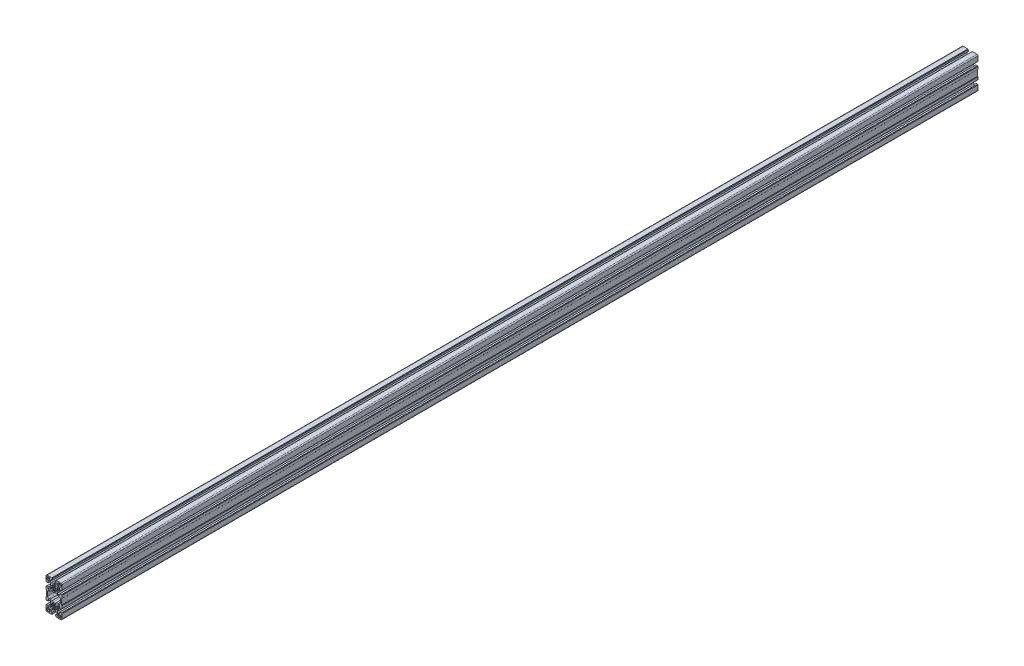
SolidWorks part; units mm, degrees
material "3.1355 (EN-AW 2024)"
ref_plane "Спереди" through (0, 0, 0) normal (0, 0, 1) x (1, 0, 0)
ref_plane "Сверху" through (0, 0, 0) normal (0, 1, 0) x (1, 0, 0)
ref_plane "Справа" through (0, 0, 0) normal (1, 0, 0) x (0, 0, -1)
sketch "Model" plane through (0, 0, 0) normal (0, 0, 1) x (1, 0, 0)
  line L360 (15.75, -42.1999) -> (15.4036, -41.9999)
  line L361 (15.4036, -41.9999) -> (13, -41.9999)
  line L362 (12, -41) -> (12, -35.5)
  line L363 (13, -34.5) -> (18.5, -34.5)
  line L364 (19.5, -35.5) -> (19.5, -41)
  line L365 (18.5, -41.9999) -> (16.0964, -41.9999)
  line L366 (16.0964, -41.9999) -> (15.75, -42.1999)
  line L367 (-19.4998, 35.4999) -> (-19.4998, 40.9999)
  line L368 (-18.4998, 41.9998) -> (-12.9998, 41.9998)
  line L369 (-11.9998, 40.9999) -> (-11.9998, 35.4999)
  line L370 (-12.9998, 34.4999) -> (-18.4998, 34.4999)
  line L371 (0.8683, -17.576) -> (1.3893, -14.6216)
  line L372 (4.5887, -15.9468) -> (2.8679, -18.4043)
  line L373 (4.0958, -19.6321) -> (6.5533, -17.9114)
  line L374 (7.8785, -21.1108) -> (4.9241, -21.6318)
  line L375 (4.9241, -23.3682) -> (7.8785, -23.8892)
  line L376 (6.5533, -27.0886) -> (4.0958, -25.3679)
  line L377 (2.868, -26.5958) -> (4.5887, -29.0532)
  line L378 (1.3893, -30.3784) -> (0.8683, -27.424)
  line L379 (-0.8682, -27.424) -> (-1.3891, -30.3785)
  line L380 (-4.5885, -29.0532) -> (-2.8678, -26.5958)
  line L381 (-4.0957, -25.3679) -> (-6.5531, -27.0886)
  line L382 (-7.8784, -23.8892) -> (-4.924, -23.3682)
  line L383 (-4.924, -21.6318) -> (-7.8784, -21.1108)
  line L384 (-6.5531, -17.9114) -> (-4.0957, -19.6321)
  line L385 (-2.8678, -18.4043) -> (-4.5885, -15.9468)
  line L386 (-1.3891, -14.6216) -> (-0.8682, -17.576)
  line L387 (14, -9.4501) -> (11.0574, -9.4501)
  line L388 (11.0574, -9.4501) -> (7.5074, -13.0001)
  line L389 (7.5074, -13.0001) -> (3.1226, -13.0001)
  line L390 (-3.1223, -13) -> (-7.5073, -13)
  line L391 (-7.5073, -13) -> (-11.0573, -9.4501)
  line L392 (-11.0573, -9.4501) -> (-13.9999, -9.4501)
  line L393 (-17.9999, -5.4501) -> (-17.9999, -5.45)
  line L394 (-17.9999, -5.45) -> (-17.9999, 5.45)
  line L395 (-13.9999, 9.45) -> (-11.0573, 9.45)
  line L396 (-11.0573, 9.45) -> (-7.5073, 12.9999)
  line L397 (-7.5073, 12.9999) -> (-3.1223, 12.9999)
  line L398 (3.1226, 13) -> (7.5074, 13)
  line L399 (7.5074, 13) -> (11.0574, 9.45)
  line L400 (11.0574, 9.45) -> (14, 9.45)
  line L401 (18, 5.4499) -> (18, -5.4501)
  line L402 (1.3893, 14.6215) -> (0.8683, 17.5759)
  line L403 (-0.8682, 17.5759) -> (-1.3891, 14.6215)
  line L404 (-4.5885, 15.9467) -> (-2.8678, 18.4042)
  line L405 (-4.0957, 19.632) -> (-6.5531, 17.9113)
  line L406 (-7.8784, 21.1107) -> (-4.924, 21.6317)
  line L407 (-4.924, 23.3681) -> (-7.8784, 23.8891)
  line L408 (-6.5531, 27.0885) -> (-4.0957, 25.3678)
  line L409 (-2.8678, 26.5957) -> (-4.5885, 29.0531)
  line L410 (-1.3891, 30.3784) -> (-0.8682, 27.4239)
  line L411 (0.8683, 27.4239) -> (1.3893, 30.3783)
  line L412 (4.5887, 29.0531) -> (2.868, 26.5957)
  line L413 (4.0958, 25.3678) -> (6.5533, 27.0885)
  line L414 (7.8785, 23.8891) -> (4.9241, 23.3681)
  line L415 (4.9241, 21.6317) -> (7.8785, 21.1107)
  line L416 (6.5533, 17.9113) -> (4.0958, 19.632)
  line L417 (2.8679, 18.4042) -> (4.5887, 15.9467)
  line L418 (18.5, 34.4999) -> (13, 34.4999)
  line L419 (12, 35.4999) -> (12, 40.9999)
  line L420 (13, 41.9998) -> (18.5, 41.9998)
  line L421 (19.5, 40.9999) -> (19.5, 35.4999)
  line L422 (-18.4998, -34.5) -> (-12.9998, -34.5)
  line L423 (-11.9998, -35.5) -> (-11.9998, -41)
  line L424 (-12.9998, -41.9999) -> (-18.4998, -41.9999)
  line L425 (-19.4998, -41) -> (-19.4998, -35.5)
  line L426 (-9.9671, -21.6906) -> (-9.4999, -22.4998)
  line L427 (-9.4999, -22.4998) -> (-9.9671, -23.3091)
  line L428 (-9.4999, -25.6225) -> (-9.4999, -29.7069)
  line L429 (-9.4999, -29.7069) -> (-12.3428, -32.5498)
  line L430 (-12.3428, -32.5498) -> (-16.4999, -32.5498)
  line L431 (-16.4999, -32.5498) -> (-16.4999, -27.6503)
  line L432 (-16.4999, -27.6503) -> (-20.9999, -27.6503)
  line L433 (-20.9999, -27.6503) -> (-20.9999, -28.2998)
  line L434 (-20.9999, -28.2998) -> (-22, -28.2998)
  line L435 (-22.5, -28.7998) -> (-22.5, -42.0001)
  line L436 (-19.5, -45.0001) -> (-6.3001, -45.0001)
  line L437 (-5.8001, -44.5001) -> (-5.8001, -43.4999)
  line L438 (-5.8001, -43.4999) -> (-5.15, -43.4999)
  line L439 (-5.15, -43.4999) -> (-5.15, -39)
  line L440 (-5.15, -39) -> (-10.05, -39)
  line L441 (-10.05, -39) -> (-10.05, -34.8429)
  line L442 (-10.05, -34.8429) -> (-7.207, -31.9999)
  line L443 (-7.207, -31.9999) -> (-3.1227, -31.9999)
  line L444 (-0.8092, -32.4672) -> (0, -32)
  line L445 (0, -32) -> (0.8092, -32.4672)
  line L446 (3.1227, -31.9999) -> (7.207, -31.9999)
  line L447 (7.207, -31.9999) -> (10.05, -34.8429)
  line L448 (10.05, -34.8429) -> (10.05, -39)
  line L449 (10.05, -39) -> (5.1501, -39)
  line L450 (5.1501, -39) -> (5.1501, -43.4999)
  line L451 (5.1501, -43.4999) -> (5.8002, -43.4999)
  line L452 (5.8002, -43.4999) -> (5.8002, -44.5001)
  line L453 (6.3002, -45.0001) -> (19.5001, -45.0001)
  line L454 (22.5, -42.0001) -> (22.5, -28.8001)
  line L455 (22, -28.3001) -> (21.0001, -28.3001)
  line L456 (21.0001, -28.3001) -> (21.0001, -27.6501)
  line L457 (21.0001, -27.6501) -> (16.5, -27.6501)
  line L458 (16.5, -27.6501) -> (16.5, -32.5501)
  line L459 (16.5, -32.5501) -> (12.3429, -32.5501)
  line L460 (12.3429, -32.5501) -> (9.5, -29.7071)
  line L461 (9.5, -29.7071) -> (9.5, -25.6228)
  line L462 (9.9672, -23.3093) -> (9.5, -22.5001)
  line L463 (9.5, -22.5001) -> (9.9672, -21.6909)
  line L464 (9.5, -19.3774) -> (9.5, -15.2931)
  line L465 (9.5, -15.2931) -> (12.3429, -12.4501)
  line L466 (12.3429, -12.4501) -> (16.5, -12.4501)
  line L467 (16.5, -12.4501) -> (16.5, -17.3501)
  line L468 (16.5, -17.3501) -> (21, -17.3501)
  line L469 (21, -17.3501) -> (21, -16.7)
  line L470 (21, -16.7) -> (22, -16.7)
  line L471 (22.5, -16.2) -> (22.5, -9.25)
  line L472 (22, -8.75) -> (21, -8.75)
  line L473 (21, -8.75) -> (21, 8.7499)
  line L474 (21, 8.7499) -> (22, 8.7499)
  line L475 (22.5, 9.2499) -> (22.5, 16.1999)
  line L476 (22, 16.6999) -> (21, 16.6999)
  line L477 (21, 16.6999) -> (21, 17.35)
  line L478 (21, 17.35) -> (16.5, 17.35)
  line L479 (16.5, 17.35) -> (16.5, 12.45)
  line L480 (16.5, 12.45) -> (12.3429, 12.45)
  line L481 (12.3429, 12.45) -> (9.5, 15.293)
  line L482 (9.5, 15.293) -> (9.5, 19.3773)
  line L483 (9.9672, 21.6908) -> (9.5, 22.5)
  line L484 (9.5, 22.5) -> (9.9672, 23.3092)
  line L485 (9.5, 25.6227) -> (9.5, 29.707)
  line L486 (9.5, 29.707) -> (12.3429, 32.55)
  line L487 (12.3429, 32.55) -> (16.5, 32.55)
  line L488 (16.5, 32.55) -> (16.5, 27.65)
  line L489 (16.5, 27.65) -> (21, 27.65)
  line L490 (21, 27.65) -> (21, 28.3)
  line L491 (21, 28.3) -> (22, 28.3)
  line L492 (22.5, 28.8) -> (22.5, 42)
  line L493 (19.5001, 44.9999) -> (6.3002, 44.9999)
  line L494 (5.8002, 44.5) -> (5.8002, 43.4998)
  line L495 (5.8002, 43.4998) -> (5.1501, 43.4998)
  line L496 (5.1501, 43.4998) -> (5.1501, 38.9998)
  line L497 (5.1501, 38.9998) -> (10.05, 38.9998)
  line L498 (10.05, 38.9998) -> (10.05, 34.8428)
  line L499 (10.05, 34.8428) -> (7.207, 31.9998)
  line L500 (7.207, 31.9998) -> (3.1227, 31.9998)
  line L501 (0.8092, 32.4671) -> (0, 31.9999)
  line L502 (0, 31.9999) -> (-0.8092, 32.4671)
  line L503 (-3.1227, 31.9998) -> (-7.207, 31.9998)
  line L504 (-7.207, 31.9998) -> (-10.05, 34.8428)
  line L505 (-10.05, 34.8428) -> (-10.05, 38.9998)
  line L506 (-10.05, 38.9998) -> (-5.15, 38.9998)
  line L507 (-5.15, 38.9998) -> (-5.15, 43.4998)
  line L508 (-5.15, 43.4998) -> (-5.8001, 43.4998)
  line L509 (-5.8001, 43.4998) -> (-5.8001, 44.5)
  line L510 (-6.3001, 44.9999) -> (-19.5, 44.9999)
  line L511 (-22.5, 42) -> (-22.5, 28.7997)
  line L512 (-22, 28.2997) -> (-20.9999, 28.2997)
  line L513 (-20.9999, 28.2997) -> (-20.9999, 27.6502)
  line L514 (-20.9999, 27.6502) -> (-16.4999, 27.6502)
  line L515 (-16.4999, 27.6502) -> (-16.4999, 32.5497)
  line L516 (-16.4999, 32.5497) -> (-12.3428, 32.5497)
  line L517 (-12.3428, 32.5497) -> (-9.4999, 29.7068)
  line L518 (-9.4999, 29.7068) -> (-9.4999, 25.6224)
  line L519 (-9.9671, 23.309) -> (-9.4999, 22.4997)
  line L520 (-9.4999, 22.4997) -> (-9.9671, 21.6905)
  line L521 (-9.4999, 19.3771) -> (-9.4999, 15.2927)
  line L522 (-9.4999, 15.2927) -> (-12.3428, 12.4498)
  line L523 (-12.3428, 12.4498) -> (-16.4999, 12.4498)
  line L524 (-16.4999, 12.4498) -> (-16.4999, 17.3498)
  line L525 (-16.4999, 17.3498) -> (-20.9999, 17.3498)
  line L526 (-20.9999, 17.3498) -> (-20.9999, 16.6998)
  line L527 (-20.9999, 16.6998) -> (-22, 16.6998)
  line L528 (-22.5, 16.1998) -> (-22.5, 9.2499)
  line L529 (-22, 8.7499) -> (-21, 8.7499)
  line L530 (-21, 8.7499) -> (-21, -8.75)
  line L531 (-21, -8.75) -> (-22, -8.75)
  line L532 (-22.5, -9.25) -> (-22.5, -16.1999)
  line L533 (-22, -16.6999) -> (-20.9999, -16.6999)
  line L534 (-20.9999, -16.6999) -> (-20.9999, -17.3499)
  line L535 (-20.9999, -17.3499) -> (-16.4999, -17.3499)
  line L536 (-16.4999, -17.3499) -> (-16.4999, -12.4499)
  line L537 (-16.4999, -12.4499) -> (-12.3428, -12.4499)
  line L538 (-12.3428, -12.4499) -> (-9.4999, -15.2928)
  line L539 (-9.4999, -15.2928) -> (-9.4999, -19.3772)
  arc A172 (12, -41) -> (13, -41.9999) centre (13, -41) ccw
  arc A173 (13, -34.5) -> (12, -35.5) centre (13, -35.5) ccw
  arc A174 (19.5, -35.5) -> (18.5, -34.5) centre (18.5, -35.5) ccw
  arc A175 (18.5, -41.9999) -> (19.5, -41) centre (18.5, -41) ccw
  arc A176 (-19.4998, 35.4999) -> (-18.4998, 34.4999) centre (-18.4998, 35.4999) ccw
  arc A177 (-18.4998, 41.9998) -> (-19.4998, 40.9999) centre (-18.4998, 40.9999) ccw
  arc A178 (-11.9998, 40.9999) -> (-12.9998, 41.9998) centre (-12.9998, 40.9999) ccw
  arc A179 (-12.9998, 34.4999) -> (-11.9998, 35.4999) centre (-12.9998, 35.4999) ccw
  arc A180 (4.5887, -15.9468) -> (1.3893, -14.6216) centre (0.0001, -22.5) ccw
  arc A181 (4.0958, -19.6321) -> (2.8679, -18.4043) centre (0.0001, -22.5) ccw
  arc A182 (7.8785, -21.1108) -> (6.5533, -17.9114) centre (0.0001, -22.5) ccw
  arc A183 (4.9241, -23.3682) -> (4.9241, -21.6318) centre (0.0001, -22.5) ccw
  arc A184 (6.5533, -27.0886) -> (7.8785, -23.8892) centre (0.0001, -22.5) ccw
  arc A185 (2.868, -26.5958) -> (4.0958, -25.3679) centre (0.0001, -22.5) ccw
  arc A186 (1.3893, -30.3784) -> (4.5887, -29.0532) centre (0.0001, -22.5) ccw
  arc A187 (-0.8682, -27.424) -> (0.8683, -27.424) centre (0.0001, -22.5) ccw
  arc A188 (-4.5885, -29.0532) -> (-1.3891, -30.3785) centre (0.0001, -22.5) ccw
  arc A189 (-4.0957, -25.3679) -> (-2.8678, -26.5958) centre (0.0001, -22.5) ccw
  arc A190 (-7.8784, -23.8892) -> (-6.5531, -27.0886) centre (0, -22.5) ccw
  arc A191 (-4.924, -21.6318) -> (-4.924, -23.3682) centre (0.0001, -22.5) ccw
  arc A192 (-6.5531, -17.9114) -> (-7.8784, -21.1108) centre (0, -22.5) ccw
  arc A193 (-2.8678, -18.4043) -> (-4.0957, -19.6321) centre (0.0001, -22.5) ccw
  arc A194 (-1.3891, -14.6216) -> (-4.5885, -15.9468) centre (0.0001, -22.5) ccw
  arc A195 (0.8683, -17.576) -> (-0.8682, -17.576) centre (0.0001, -22.5) ccw
  arc A196 (14, -9.4501) -> (18, -5.4501) centre (14, -5.4501) ccw
  arc A197 (3.1226, -13.0001) -> (-3.1223, -13) centre (0.0001, -22.5) ccw
  arc A198 (-17.9999, -5.4501) -> (-13.9999, -9.4501) centre (-13.9999, -5.4501) ccw
  arc A199 (-13.9999, 9.45) -> (-17.9999, 5.45) centre (-13.9999, 5.45) ccw
  arc A200 (-3.1223, 12.9999) -> (3.1226, 13) centre (0.0001, 22.4999) ccw
  arc A201 (18, 5.4499) -> (14, 9.45) centre (14, 5.45) ccw
  arc A202 (-0.8682, 17.5759) -> (0.8683, 17.5759) centre (0.0001, 22.4999) ccw
  arc A203 (-4.5885, 15.9467) -> (-1.3891, 14.6215) centre (0.0001, 22.4999) ccw
  arc A204 (-4.0957, 19.632) -> (-2.8678, 18.4042) centre (0.0001, 22.4999) ccw
  arc A205 (-7.8784, 21.1107) -> (-6.5531, 17.9113) centre (0, 22.4999) ccw
  arc A206 (-4.924, 23.3681) -> (-4.924, 21.6317) centre (0.0001, 22.4999) ccw
  arc A207 (-6.5531, 27.0885) -> (-7.8784, 23.8891) centre (0, 22.4999) ccw
  arc A208 (-2.8678, 26.5957) -> (-4.0957, 25.3678) centre (0.0001, 22.4999) ccw
  arc A209 (-1.3891, 30.3784) -> (-4.5885, 29.0531) centre (0.0001, 22.4999) ccw
  arc A210 (0.8683, 27.4239) -> (-0.8682, 27.4239) centre (0.0001, 22.4999) ccw
  arc A211 (4.5887, 29.0531) -> (1.3893, 30.3783) centre (0.0001, 22.4999) ccw
  arc A212 (4.0958, 25.3678) -> (2.868, 26.5957) centre (0.0001, 22.4999) ccw
  arc A213 (7.8785, 23.8891) -> (6.5533, 27.0885) centre (0.0001, 22.4999) ccw
  arc A214 (4.9241, 21.6317) -> (4.9241, 23.3681) centre (0.0001, 22.4999) ccw
  arc A215 (6.5533, 17.9113) -> (7.8785, 21.1107) centre (0.0001, 22.4999) ccw
  arc A216 (2.8679, 18.4042) -> (4.0958, 19.632) centre (0.0001, 22.4999) ccw
  arc A217 (1.3893, 14.6215) -> (4.5887, 15.9467) centre (0.0001, 22.4999) ccw
  arc A218 (18.5, 34.4999) -> (19.5, 35.4999) centre (18.5, 35.4999) ccw
  arc A219 (12, 35.4999) -> (13, 34.4999) centre (13, 35.4999) ccw
  arc A220 (13, 41.9998) -> (12, 40.9999) centre (13, 40.9999) ccw
  arc A221 (19.5, 40.9999) -> (18.5, 41.9998) centre (18.5, 40.9999) ccw
  arc A222 (-18.4998, -34.5) -> (-19.4998, -35.5) centre (-18.4998, -35.5) ccw
  arc A223 (-11.9998, -35.5) -> (-12.9998, -34.5) centre (-12.9998, -35.5) ccw
  arc A224 (-12.9998, -41.9999) -> (-11.9998, -41) centre (-12.9998, -41) ccw
  arc A225 (-19.4998, -41) -> (-18.4998, -41.9999) centre (-18.4998, -41) ccw
  arc A226 (-9.9671, -23.3091) -> (-9.4999, -25.6225) centre (0, -22.4998) ccw
  arc A227 (-22, -28.2998) -> (-22.5, -28.7998) centre (-22, -28.7998) ccw
  arc A228 (-22.5, -42.0001) -> (-19.5, -45.0001) centre (-19.5, -42.0001) ccw
  arc A229 (-6.3001, -45.0001) -> (-5.8001, -44.5001) centre (-6.3001, -44.5001) ccw
  arc A230 (-3.1227, -31.9999) -> (-0.8092, -32.4672) centre (0, -22.5) ccw
  arc A231 (0.8092, -32.4672) -> (3.1227, -31.9999) centre (0, -22.5) ccw
  arc A232 (5.8002, -44.5001) -> (6.3002, -45.0001) centre (6.3002, -44.5001) ccw
  arc A233 (19.5001, -45.0001) -> (22.5, -42.0001) centre (19.5001, -42.0001) ccw
  arc A234 (22.5, -28.8001) -> (22, -28.3001) centre (22, -28.8001) ccw
  arc A235 (9.5, -25.6228) -> (9.9672, -23.3093) centre (0.0001, -22.5001) ccw
  arc A236 (9.9672, -21.6909) -> (9.5, -19.3774) centre (0.0001, -22.5001) ccw
  arc A237 (22, -16.7) -> (22.5, -16.2) centre (22, -16.2) ccw
  arc A238 (22.5, -9.25) -> (22, -8.75) centre (22, -9.25) ccw
  arc A239 (22, 8.7499) -> (22.5, 9.2499) centre (22, 9.2499) ccw
  arc A240 (22.5, 16.1999) -> (22, 16.6999) centre (22, 16.1999) ccw
  arc A241 (9.5, 19.3773) -> (9.9672, 21.6908) centre (0.0001, 22.5) ccw
  arc A242 (9.9672, 23.3092) -> (9.5, 25.6227) centre (0.0001, 22.5) ccw
  arc A243 (22, 28.3) -> (22.5, 28.8) centre (22, 28.8) ccw
  arc A244 (22.5, 42) -> (19.5001, 44.9999) centre (19.5001, 42) ccw
  arc A245 (6.3002, 44.9999) -> (5.8002, 44.5) centre (6.3002, 44.5) ccw
  arc A246 (3.1227, 31.9998) -> (0.8092, 32.4671) centre (0, 22.4999) ccw
  arc A247 (-0.8092, 32.4671) -> (-3.1227, 31.9998) centre (0, 22.4999) ccw
  arc A248 (-5.8001, 44.5) -> (-6.3001, 44.9999) centre (-6.3001, 44.5) ccw
  arc A249 (-19.5, 44.9999) -> (-22.5, 42) centre (-19.5, 42) ccw
  arc A250 (-22.5, 28.7997) -> (-22, 28.2997) centre (-22, 28.7997) ccw
  arc A251 (-9.4999, 25.6224) -> (-9.9671, 23.309) centre (0, 22.4997) ccw
  arc A252 (-9.9671, 21.6905) -> (-9.4999, 19.3771) centre (0, 22.4997) ccw
  arc A253 (-22, 16.6998) -> (-22.5, 16.1998) centre (-22, 16.1998) ccw
  arc A254 (-22.5, 9.2499) -> (-22, 8.7499) centre (-22, 9.2499) ccw
  arc A255 (-22, -8.75) -> (-22.5, -9.25) centre (-22, -9.25) ccw
  arc A256 (-22.5, -16.1999) -> (-22, -16.6999) centre (-22, -16.1999) ccw
  arc A257 (-9.4999, -19.3772) -> (-9.9671, -21.6906) centre (0, -22.4998) ccw
  dimension "D1" = 90
  dimension "D2" = 45
  dimension "D3" = 45
extrude "Бобышка-Вытянуть1" add sketch "Model" against normal blind 2600
